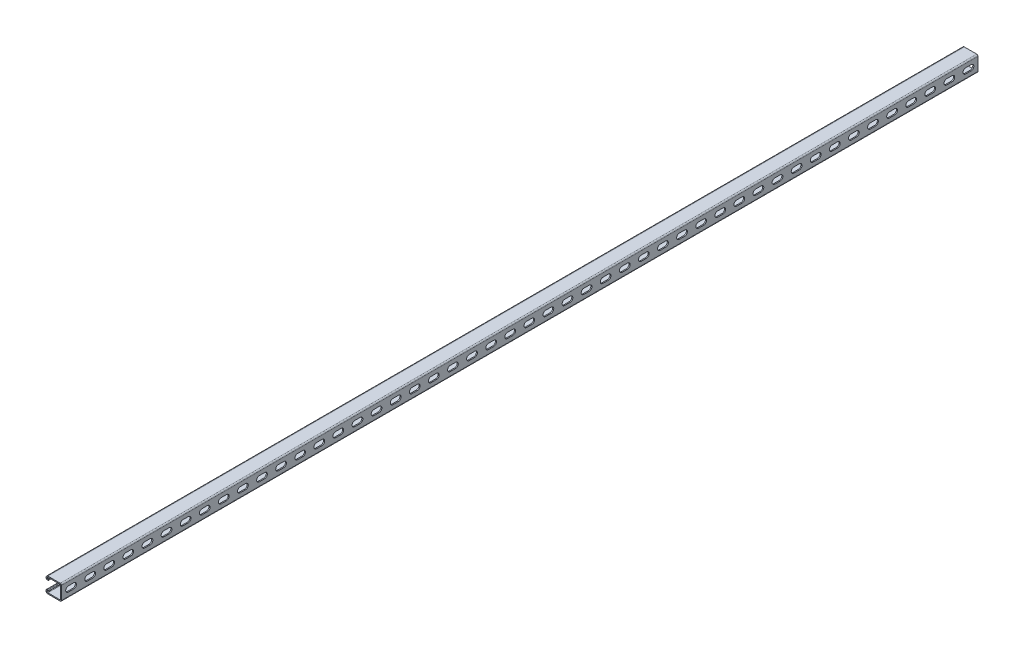
SolidWorks part; units mm, degrees
ref_plane "Front Plane" through (0, 0, 0) normal (0, 0, 1) x (1, 0, 0)
ref_plane "Top Plane" through (0, 0, 0) normal (0, 1, 0) x (1, 0, 0)
ref_plane "Right Plane" through (0, 0, 0) normal (1, 0, 0) x (0, 0, -1)
sketch "Sketch1" plane through (0, 0, 0) normal (0, 0, 1) x (1, 0, 0)
  line L0 (0, 0) -> (-41.275, 0) construction
  line L3 (-41.275, 20.6375) -> (0, 20.6375) construction
  line L4 (-41.275, 20.6375) -> (-41.275, -20.6375) construction
  line L5 (-41.275, -20.6375) -> (0, -20.6375) construction
  line L6 (0, 20.6375) -> (0, -20.6375) construction
  line L7 (-36.2267, 20.6375) -> (-3.4607, 20.6375)
  line L8 (0, 17.1767) -> (0, -17.1767)
  line L9 (-2.794, -17.1767) -> (-2.794, 17.1767)
  line L10 (-3.4608, 17.8435) -> (-36.2267, 17.8435)
  line L11 (-41.275, 15.5892) -> (-41.275, 14.5732)
  line L12 (-37.8142, 11.1125) -> (-35.5346, 11.1125)
  line L14 (-35.5346, 13.9065) -> (-37.8142, 13.9065)
  line L15 (-38.481, 14.5732) -> (-38.481, 15.5892)
  line L16 (-38.481, -14.5733) -> (-38.481, -15.5893)
  line L17 (-35.5346, -13.9065) -> (-37.8142, -13.9065)
  line L18 (-37.8142, -11.1125) -> (-35.5346, -11.1125)
  line L19 (-41.275, -15.5893) -> (-41.275, -14.5733)
  line L20 (-3.4607, -17.8435) -> (-36.2267, -17.8435)
  line L21 (-36.2267, -20.6375) -> (-3.4607, -20.6375)
  line L22 (-2.794, -20.6375) -> (-2.794, 20.6375) construction
  arc A1 (0, 17.1767) -> (-3.4607, 20.6375) centre (-3.4607, 17.1767) ccw
  arc A2 (-2.794, 17.1767) -> (-3.4608, 17.8435) centre (-3.4607, 17.1767) ccw
  arc A4 (-36.2267, 20.6375) -> (-41.275, 15.5892) centre (-36.2267, 15.5892) ccw
  arc A5 (-41.275, 14.5732) -> (-37.8142, 11.1125) centre (-37.8142, 14.5732) ccw
  arc A6 (-35.5346, 11.1125) -> (-35.5346, 13.9065) centre (-35.5346, 12.5095) ccw
  arc A7 (-37.8142, 13.9065) -> (-38.481, 14.5732) centre (-37.8142, 14.5732) cw
  arc A8 (-38.481, 15.5892) -> (-36.2267, 17.8435) centre (-36.2267, 15.5892) cw
  arc A9 (-38.481, -15.5893) -> (-36.2267, -17.8435) centre (-36.2267, -15.5893) ccw
  arc A10 (-37.8142, -13.9065) -> (-38.481, -14.5733) centre (-37.8142, -14.5733) ccw
  arc A11 (-35.5346, -11.1125) -> (-35.5346, -13.9065) centre (-35.5346, -12.5095) cw
  arc A12 (-41.275, -14.5733) -> (-37.8142, -11.1125) centre (-37.8142, -14.5733) cw
  arc A13 (-36.2267, -20.6375) -> (-41.275, -15.5893) centre (-36.2267, -15.5893) cw
  arc A14 (-2.794, -17.1767) -> (-3.4607, -17.8435) centre (-3.4607, -17.1767) cw
  arc A15 (0, -17.1767) -> (-3.4607, -20.6375) centre (-3.4607, -17.1767) cw
  point P24 (0, 20.6375)
  point P65 (-2.794, 0)
  dimension "D1" = 3.4608
  dimension "D2" = 5.0482
  dimension "D3" = 3.4608
  dimension "Ht." = 41.275
  dimension "Wd." = 41.275
  dimension "Thk." = 2.794
  dimension "D4" = 9.525
  dimension "D5" = 7.1374
extrude "Boss-Extrude1" add sketch "Sketch1" against normal blind 2438.4
sketch "Sketch3" plane through (0, 0, 0) normal (1, 0, 0) x (0, 0, -1)
  line L0 (0, 0) -> (2438.4, 0) construction
  point P2 (101.6, 0)
  point P3 (2336.8, 0)
  dimension "D1" = 101.6
  dimension "D2" = 101.6
  dimension "D3" = 2438.4
sketch "Sketch2" plane through (0, 0, 0) normal (1, 0, 0) x (0, 0, -1)
  line L0 (18.2562, 0) -> (32.5437, 0) construction
  line L1 (18.2562, 7.1437) -> (32.5437, 7.1437)
  line L2 (18.2562, -7.1437) -> (32.5437, -7.1437)
  line L3 (18.2562, 0) -> (0, 0) construction
  line L4 (25.4, 0) -> (76.2, 0) construction
  line L5 (0, -17.1767) -> (0, 17.1767) construction
  arc A0 (18.2562, 7.1437) -> (18.2562, -7.1437) centre (18.2562, 0) ccw
  arc A1 (32.5437, -7.1437) -> (32.5437, 7.1437) centre (32.5437, 0) ccw
  point P3 (25.4, 0)
  dimension "Hole to End" = 11.1125
  dimension "D2" = 25.4
extrude "Cut-Extrude1" cut sketch "Sketch2" against normal up to vertex (2.794 mm away) up to point (-2.794, 0, 0)
pattern_linear "LPattern1" count 48 spacing 50.8 along (0, 0, -1) of "Cut-Extrude1"
equation "\"D1@LPattern1\" = \"Slot Ctr.@Sketch2\""
equation "\"Hole Count@LPattern1\" = \"Lg.@Boss-Extrude1\" / \"D1@LPattern1\""
equation "\"D3@Sketch3\" = \"Lg.@Boss-Extrude1\""
